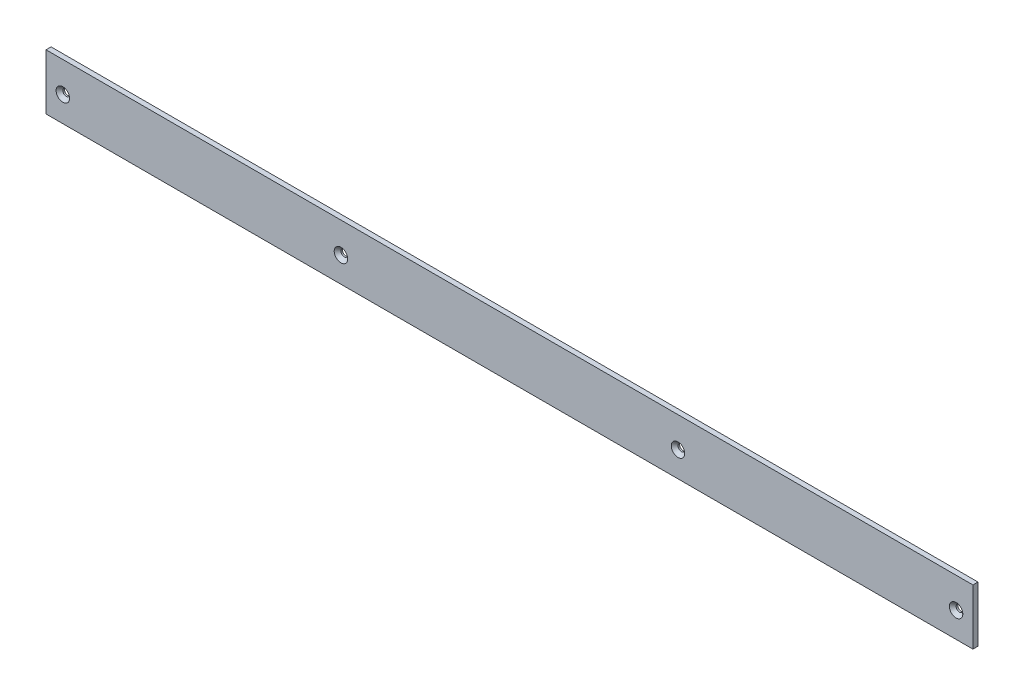
SolidWorks part; units mm, degrees
ref_plane "前视基准面" through (0, 0, 0) normal (0, 0, 1) x (1, 0, 0)
ref_plane "上视基准面" through (0, 0, 0) normal (0, 1, 0) x (1, 0, 0)
ref_plane "右视基准面" through (0, 0, 0) normal (1, 0, 0) x (0, 0, -1)
sketch "草图1" plane through (0, 0, 0) normal (0, 0, 1) x (1, 0, 0)
  line L1 (-275, 16.5) -> (275, 16.5)
  line L2 (-275, 16.5) -> (-275, -16.5)
  line L3 (-275, -16.5) -> (275, -16.5)
  line L4 (275, 16.5) -> (275, -16.5)
  point P4 (0, 16.5)
  point P7 (275, 0)
  dimension "D1" = 550
  dimension "D2" = 33
extrude "凸台-拉伸1" add sketch "草图1" along normal blind 3
sketch "草图2" plane through (0, 0, 0) normal (0, 0, 1) x (1, 0, 0)
  line L0 (-275, -16.5) -> (275, -16.5) construction
  line L1 (0, -16.5) -> (0, 16.5) construction
  line L2 (275, 16.5) -> (-275, 16.5) construction
  line L3 (-275, 16.5) -> (-275, -16.5) construction
  circle A0 centre (-265, -1.5) radius 2
  circle A1 centre (-100, -1.5) radius 2
  circle A2 centre (100, -1.5) radius 2
  circle A3 centre (265, -1.5) radius 2
  dimension "D3" = 4
  dimension "D1" = 100
  dimension "D2" = 10
  dimension "D4" = 15
extrude "切除-拉伸2" cut sketch "草图2" along normal through all
chamfer "倒角1" distance 2 angle 45 4 edges at (263, -1.5, 3) (98, -1.5, 3) (-98, -1.5, 3) (-263, -1.5, 3)
